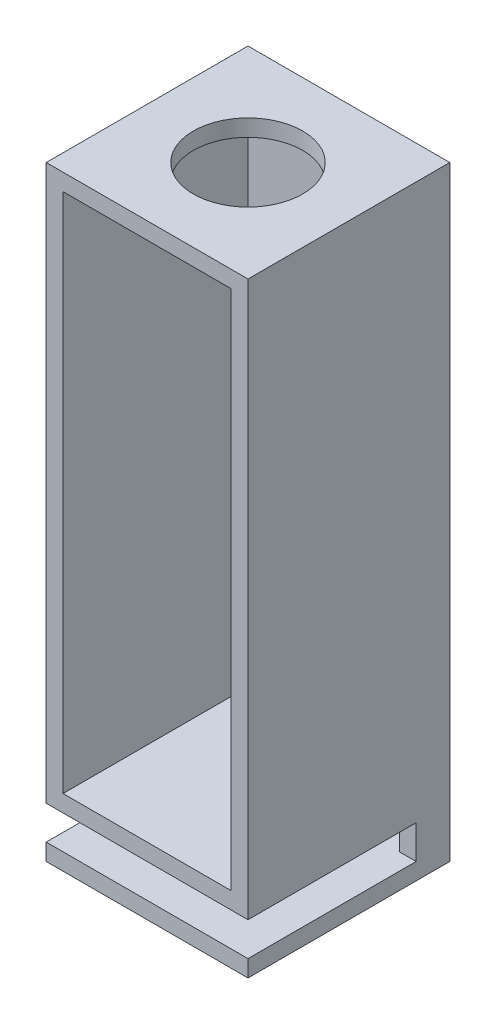
SolidWorks part; units mm, degrees
ref_plane "Alzado" through (0, 0, 0) normal (0, 0, 1) x (1, 0, 0)
ref_plane "Planta" through (0, 0, 0) normal (0, 1, 0) x (1, 0, 0)
ref_plane "Vista lateral" through (0, 0, 0) normal (1, 0, 0) x (0, 0, -1)
sketch "Croquis1" plane through (0, 0, 0) normal (0, 1, 0) x (1, 0, 0)
  line L1 (-6, 6) -> (6, 6)
  line L2 (-6, 6) -> (-6, -6)
  line L3 (-6, -6) -> (6, -6)
  line L4 (6, 6) -> (6, -6)
  line L5 (-6, 6) -> (6, -6) construction
  line L6 (-6, -6) -> (6, 6) construction
  point P0 (0, 0)
  dimension "D1" = 12
  dimension "D2" = 12
extrude "Saliente-Extruir1" add sketch "Croquis1" along normal blind 36
shell "Vaciado1" thickness 1
sketch "Croquis2" plane through (0, 36, 0) normal (0, 1, 0) x (1, 0, 0)
  circle A0 centre (0, 0) radius 3.25
  dimension "D1" = 6.5
extrude "Cortar-Extruir1" cut sketch "Croquis2" against normal blind 3 and the other way through all
sketch "Croquis3" plane through (0, 0, 6) normal (0, 0, 1) x (1, 0, 0)
  line L1 (-6.7727, 1) -> (6.8802, 1)
  line L2 (-6.7727, 1) -> (-6.7727, 3)
  line L3 (-6.7727, 3) -> (6.8802, 3)
  line L4 (6.8802, 1) -> (6.8802, 3)
  line L5 (-6, 0) -> (6, 0) construction
  dimension "D1" = 2
  dimension "D2" = 1
extrude "Cortar-Extruir2" cut sketch "Croquis3" against normal blind 10
sketch "Croquis4" plane through (0, 0, 6) normal (0, 0, 1) x (1, 0, 0)
  line L0 (5, 35) -> (5, 3) construction
  line L1 (-5, 3) -> (5, 3)
  line L2 (-5, 3) -> (-5, 4)
  line L3 (-5, 4) -> (5, 4)
  line L4 (5, 3) -> (5, 4)
  dimension "D1" = 1
extrude "Saliente-Extruir2" add sketch "Croquis4" against normal up to surface (11 mm away) up to face at (0, 18, -5)
